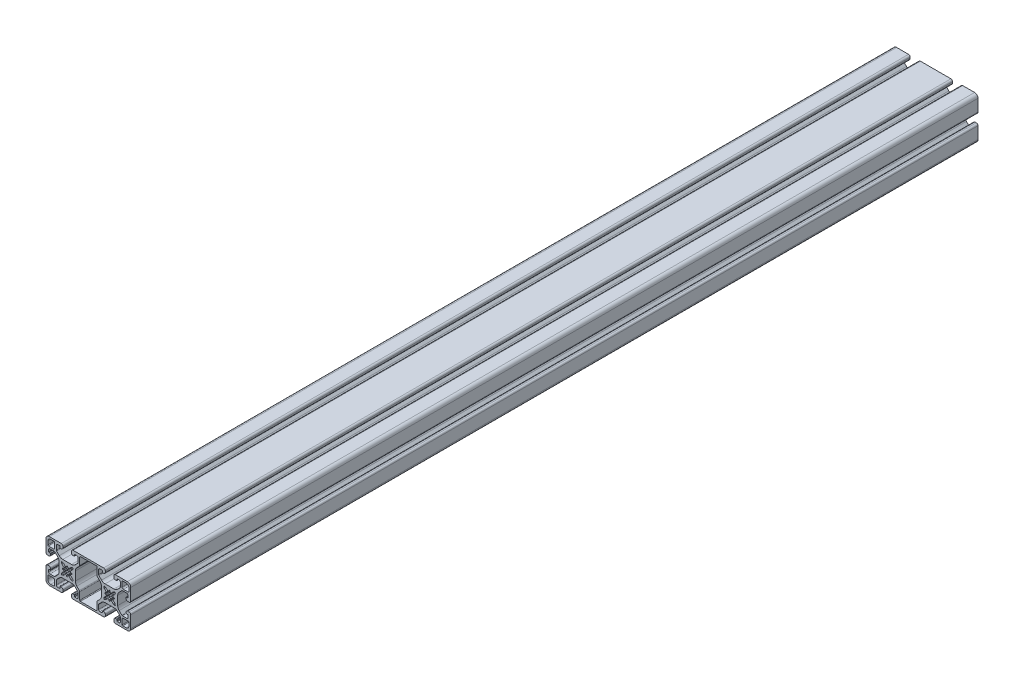
SolidWorks part; units mm, degrees
material "6105-T5 Aluminum"
ref_plane "Front Plane" through (0, 0, 0) normal (0, 0, 1) x (1, 0, 0)
ref_plane "Top Plane" through (0, 0, 0) normal (0, 1, 0) x (1, 0, 0)
ref_plane "Right Plane" through (0, 0, 0) normal (1, 0, 0) x (0, 0, -1)
sketch "Sketch1" plane through (0, 0, 0) normal (0, 0, 1) x (1, 0, 0)
  line L0 (-44, -18.4848) -> (-44, -17.255)
  line L1 (-46.474, -15.685) -> (-45.57, -15.685)
  line L2 (-56.83, -20) -> (-45.569, -20)
  line L3 (-46.855, -17.119) -> (-46.855, -16.066)
  line L4 (-60, -16.83) -> (-60, -5.57)
  line L5 (-49.015, -17.5) -> (-47.236, -17.5)
  line L6 (-58.43, -4) -> (-57.255, -4)
  line L7 (-50.285, -16.23) -> (-50.285, -12.2162)
  line L8 (-55.685, -5.57) -> (-55.685, -6.474)
  line L9 (-47.5137, -9.0762) -> (-50.0243, -11.5869)
  line L10 (-57.119, -6.855) -> (-56.066, -6.855)
  line L11 (-44.1549, -7.685) -> (-35.8451, -7.685)
  line L12 (-57.5, -9.015) -> (-57.5, -7.236)
  line L13 (-32.4863, -9.0762) -> (-29.9757, -11.5869)
  line L14 (-56.23, -10.285) -> (-52.2162, -10.285)
  line L15 (-29.715, -16.23) -> (-29.715, -12.2162)
  line L16 (-49.0762, -7.5137) -> (-51.5869, -10.0243)
  line L17 (-30.985, -17.5) -> (-32.764, -17.5)
  line L18 (-47.685, 4.1549) -> (-47.685, -4.1549)
  line L19 (-33.145, -17.119) -> (-33.145, -16.066)
  line L20 (-49.0762, 7.5137) -> (-51.5869, 10.0243)
  line L21 (-34.43, -15.685) -> (-33.526, -15.685)
  line L22 (-56.23, 10.285) -> (-52.2162, 10.285)
  line L23 (-36, -18.4848) -> (-36, -17.255)
  line L24 (-57.5, 9.015) -> (-57.5, 7.236)
  line L25 (-5.57, -20) -> (-34.431, -20)
  line L26 (-57.119, 6.855) -> (-56.066, 6.855)
  line L27 (-4, -17.255) -> (-4, -18.43)
  line L28 (-55.685, 6.474) -> (-55.685, 5.57)
  line L29 (-5.57, -15.685) -> (-6.474, -15.685)
  line L30 (-58.43, 4) -> (-57.255, 4)
  line L31 (-6.855, -17.119) -> (-6.855, -16.066)
  line L32 (-60, 16.83) -> (-60, 5.57)
  line L33 (-9.015, -17.5) -> (-7.236, -17.5)
  line L34 (-56.83, 20) -> (-45.57, 20)
  line L35 (-10.285, -16.23) -> (-10.285, -12.2162)
  line L36 (-44, 18.43) -> (-44, 17.255)
  line L37 (-7.5137, -9.0762) -> (-10.0243, -11.5869)
  line L38 (-45.57, 15.685) -> (-46.474, 15.685)
  line L39 (4.1549, -7.685) -> (-4.1549, -7.685)
  line L40 (-46.855, 17.119) -> (-46.855, 16.066)
  line L41 (7.5137, -9.0762) -> (10.0243, -11.5869)
  line L42 (-49.015, 17.5) -> (-47.236, 17.5)
  line L43 (10.285, -16.23) -> (10.285, -12.2162)
  line L44 (-50.285, 16.23) -> (-50.285, 12.2162)
  line L45 (9.015, -17.5) -> (7.236, -17.5)
  line L46 (-47.5137, 9.0762) -> (-50.0243, 11.5869)
  line L47 (6.855, -17.119) -> (6.855, -16.066)
  line L48 (-35.8451, 7.685) -> (-44.1549, 7.685)
  line L49 (6.474, -15.685) -> (5.57, -15.685)
  line L50 (-32.4863, 9.0762) -> (-29.9757, 11.5869)
  line L51 (4, -17.255) -> (4, -18.43)
  line L52 (-29.715, 16.23) -> (-29.715, 12.2162)
  line L53 (16.83, -20) -> (5.57, -20)
  line L54 (-30.985, 17.5) -> (-32.764, 17.5)
  line L55 (20, -16.83) -> (20, -5.57)
  line L56 (-33.145, 17.119) -> (-33.145, 16.066)
  line L57 (17.255, -4) -> (18.43, -4)
  line L58 (-33.526, 15.685) -> (-34.43, 15.685)
  line L59 (15.685, -5.57) -> (15.685, -6.474)
  line L60 (-36, 18.43) -> (-36, 17.255)
  line L61 (17.119, -6.855) -> (16.066, -6.855)
  line L62 (-34.43, 20) -> (-5.57, 20)
  line L63 (17.5, -9.015) -> (17.5, -7.236)
  line L64 (-4, 18.43) -> (-4, 17.255)
  line L65 (16.23, -10.285) -> (12.2162, -10.285)
  line L66 (-6.474, 15.685) -> (-5.57, 15.685)
  line L67 (9.0762, -7.5137) -> (11.5869, -10.0243)
  line L68 (-6.855, 17.119) -> (-6.855, 16.066)
  line L69 (7.685, 4.1549) -> (7.685, -4.1549)
  line L70 (-9.015, 17.5) -> (-7.236, 17.5)
  line L71 (9.0762, 7.5137) -> (11.5869, 10.0243)
  line L72 (-10.285, 16.23) -> (-10.285, 12.2162)
  line L73 (16.23, 10.285) -> (12.2162, 10.285)
  line L74 (-7.5137, 9.0762) -> (-10.0243, 11.5869)
  line L75 (17.5, 9.015) -> (17.5, 7.236)
  line L76 (-4.1549, 7.685) -> (4.1549, 7.685)
  line L77 (17.119, 6.855) -> (16.066, 6.855)
  line L78 (7.5137, 9.0762) -> (10.0243, 11.5869)
  line L79 (15.685, 6.474) -> (15.685, 5.57)
  line L80 (10.285, 16.23) -> (10.285, 12.2162)
  line L81 (17.255, 4) -> (18.43, 4)
  line L82 (9.015, 17.5) -> (7.236, 17.5)
  line L83 (20, 16.83) -> (20, 5.57)
  line L84 (6.855, 17.119) -> (6.855, 16.066)
  line L85 (16.83, 20) -> (5.57, 20)
  line L86 (5.57, 15.685) -> (6.474, 15.685)
  line L87 (4, 18.43) -> (4, 17.255)
  line L88 (15.545, -18.345) -> (12.4898, -18.345)
  line L89 (18.345, -12.4898) -> (18.345, -15.545)
  line L90 (11.8598, -17.715) -> (11.8598, -13.1298)
  line L91 (13.1298, -11.8598) -> (17.715, -11.8598)
  line L92 (-11.8598, 17.715) -> (-11.8598, 10.8233)
  line L93 (-11.4878, 9.9253) -> (-9.0762, 7.5137)
  line L94 (-27.5102, 18.345) -> (-12.4898, 18.345)
  line L95 (-7.685, 4.1549) -> (-7.685, -4.1549)
  line L96 (-28.1402, 10.8233) -> (-28.1402, 17.715)
  line L97 (-9.0762, -7.5137) -> (-11.4878, -9.9253)
  line L98 (-30.9238, 7.5137) -> (-28.5122, 9.9253)
  line L99 (-11.8598, -10.8233) -> (-11.8598, -17.715)
  line L100 (-32.315, -4.1549) -> (-32.315, 4.1549)
  line L101 (-12.4898, -18.345) -> (-27.5102, -18.345)
  line L102 (-28.5122, -9.9253) -> (-30.9238, -7.5137)
  line L103 (-28.1402, -17.715) -> (-28.1402, -10.8233)
  line L104 (-58.345, -15.545) -> (-58.345, -12.4898)
  line L105 (-52.4898, -18.345) -> (-55.545, -18.345)
  line L106 (-57.715, -11.8598) -> (-53.1298, -11.8598)
  line L107 (-51.8598, -13.1298) -> (-51.8598, -17.715)
  line L108 (-55.545, 18.345) -> (-52.4898, 18.345)
  line L109 (-58.345, 12.4898) -> (-58.345, 15.545)
  line L110 (-51.8598, 17.715) -> (-51.8598, 13.1298)
  line L111 (-53.1298, 11.8598) -> (-57.715, 11.8598)
  line L112 (18.345, 15.545) -> (18.345, 12.4898)
  line L113 (12.4898, 18.345) -> (15.545, 18.345)
  line L114 (17.715, 11.8598) -> (13.1298, 11.8598)
  line L115 (11.8598, 13.1298) -> (11.8598, 17.715)
  line L116 (-34.8737, -3.712) -> (-34.5607, -4.8481)
  line L117 (-36.9951, -1.5907) -> (-34.8737, -3.712)
  line L118 (-35.1519, -5.4393) -> (-36.288, -5.1263)
  line L119 (-36.288, -5.1263) -> (-38.4093, -3.0049)
  line L120 (-35.9124, -0.4923) -> (-36.6579, -0.625)
  line L121 (-39.375, -3.3421) -> (-39.5077, -4.0876)
  line L122 (-36.6579, 0.625) -> (-35.9124, 0.4923)
  line L123 (-40.4923, -4.0876) -> (-40.625, -3.3421)
  line L124 (-34.8737, 3.712) -> (-36.9951, 1.5907)
  line L125 (-34.5607, 4.8481) -> (-34.8737, 3.712)
  line L126 (-41.5907, -3.0049) -> (-43.712, -5.1263)
  line L127 (-43.712, -5.1263) -> (-44.8481, -5.4393)
  line L128 (-36.288, 5.1263) -> (-35.1519, 5.4393)
  line L129 (-38.4093, 3.0049) -> (-36.288, 5.1263)
  line L130 (-45.4393, -4.8481) -> (-45.1263, -3.712)
  line L131 (-45.1263, -3.712) -> (-43.0049, -1.5907)
  line L132 (-39.5077, 4.0876) -> (-39.375, 3.3421)
  line L133 (-43.3421, -0.625) -> (-44.0876, -0.4923)
  line L134 (-40.625, 3.3421) -> (-40.4923, 4.0876)
  line L135 (-44.0876, 0.4923) -> (-43.3421, 0.625)
  line L136 (-43.712, 5.1263) -> (-41.5907, 3.0049)
  line L137 (-44.8481, 5.4393) -> (-43.712, 5.1263)
  line L138 (-43.0049, 1.5907) -> (-45.1263, 3.712)
  line L139 (-45.1263, 3.712) -> (-45.4393, 4.8481)
  line L140 (5.1263, -3.712) -> (5.4393, -4.8481)
  line L141 (3.0049, -1.5907) -> (5.1263, -3.712)
  line L142 (4.8481, -5.4393) -> (3.712, -5.1263)
  line L143 (3.712, -5.1263) -> (1.5907, -3.0049)
  line L144 (4.0876, -0.4923) -> (3.3421, -0.625)
  line L145 (0.625, -3.3421) -> (0.4923, -4.0876)
  line L146 (3.3421, 0.625) -> (4.0876, 0.4923)
  line L147 (-0.4923, -4.0876) -> (-0.625, -3.3421)
  line L148 (5.1263, 3.712) -> (3.0049, 1.5907)
  line L149 (5.4393, 4.8481) -> (5.1263, 3.712)
  line L150 (-1.5907, -3.0049) -> (-3.712, -5.1263)
  line L151 (-3.712, -5.1263) -> (-4.8481, -5.4393)
  line L152 (3.712, 5.1263) -> (4.8481, 5.4393)
  line L153 (1.5907, 3.0049) -> (3.712, 5.1263)
  line L154 (-5.4393, -4.8481) -> (-5.1263, -3.712)
  line L155 (-5.1263, -3.712) -> (-3.0049, -1.5907)
  line L156 (0.4923, 4.0876) -> (0.625, 3.3421)
  line L157 (-3.3421, -0.625) -> (-4.0876, -0.4923)
  line L158 (-0.625, 3.3421) -> (-0.4923, 4.0876)
  line L159 (-4.0876, 0.4923) -> (-3.3421, 0.625)
  line L160 (-3.712, 5.1263) -> (-1.5907, 3.0049)
  line L161 (-4.8481, 5.4393) -> (-3.712, 5.1263)
  line L162 (-3.0049, 1.5907) -> (-5.1263, 3.712)
  line L163 (-5.1263, 3.712) -> (-5.4393, 4.8481)
  arc A0 (-44, -17.255) -> (-45.57, -15.685) centre (-45.57, -17.255) ccw
  arc A1 (-45.569, -20) -> (-44, -18.4848) centre (-45.569, -18.43) ccw
  arc A2 (-46.474, -15.685) -> (-46.855, -16.066) centre (-46.474, -16.066) ccw
  arc A3 (-60, -16.83) -> (-56.83, -20) centre (-56.83, -16.83) ccw
  arc A4 (-47.236, -17.5) -> (-46.855, -17.119) centre (-47.236, -17.119) ccw
  arc A5 (-58.43, -4) -> (-60, -5.57) centre (-58.43, -5.57) ccw
  arc A6 (-50.285, -16.23) -> (-49.015, -17.5) centre (-49.015, -16.23) ccw
  arc A7 (-55.685, -5.57) -> (-57.255, -4) centre (-57.255, -5.57) ccw
  arc A8 (-50.0243, -11.5869) -> (-50.285, -12.2162) centre (-49.395, -12.2162) ccw
  arc A9 (-56.066, -6.855) -> (-55.685, -6.474) centre (-56.066, -6.474) ccw
  arc A10 (-44.1549, -7.685) -> (-47.5137, -9.0762) centre (-44.1549, -12.435) ccw
  arc A11 (-57.119, -6.855) -> (-57.5, -7.236) centre (-57.119, -7.236) ccw
  arc A12 (-32.4863, -9.0762) -> (-35.8451, -7.685) centre (-35.8451, -12.435) ccw
  arc A13 (-57.5, -9.015) -> (-56.23, -10.285) centre (-56.23, -9.015) ccw
  arc A14 (-29.715, -12.2162) -> (-29.9757, -11.5869) centre (-30.605, -12.2162) ccw
  arc A15 (-52.2162, -10.285) -> (-51.5869, -10.0243) centre (-52.2162, -9.395) ccw
  arc A16 (-30.985, -17.5) -> (-29.715, -16.23) centre (-30.985, -16.23) ccw
  arc A17 (-49.0762, -7.5137) -> (-47.685, -4.1549) centre (-52.435, -4.1549) ccw
  arc A18 (-33.145, -17.119) -> (-32.764, -17.5) centre (-32.764, -17.119) ccw
  arc A19 (-47.685, 4.1549) -> (-49.0762, 7.5137) centre (-52.435, 4.1549) ccw
  arc A20 (-33.145, -16.066) -> (-33.526, -15.685) centre (-33.526, -16.066) ccw
  arc A21 (-51.5869, 10.0243) -> (-52.2162, 10.285) centre (-52.2162, 9.395) ccw
  arc A22 (-34.43, -15.685) -> (-36, -17.255) centre (-34.43, -17.255) ccw
  arc A23 (-56.23, 10.285) -> (-57.5, 9.015) centre (-56.23, 9.015) ccw
  arc A24 (-36, -18.4848) -> (-34.431, -20) centre (-34.431, -18.43) ccw
  arc A25 (-57.5, 7.236) -> (-57.119, 6.855) centre (-57.119, 7.236) ccw
  arc A26 (-5.57, -20) -> (-4, -18.43) centre (-5.57, -18.43) ccw
  arc A27 (-55.685, 6.474) -> (-56.066, 6.855) centre (-56.066, 6.474) ccw
  arc A28 (-4, -17.255) -> (-5.57, -15.685) centre (-5.57, -17.255) ccw
  arc A29 (-57.255, 4) -> (-55.685, 5.57) centre (-57.255, 5.57) ccw
  arc A30 (-6.474, -15.685) -> (-6.855, -16.066) centre (-6.474, -16.066) ccw
  arc A31 (-60, 5.57) -> (-58.43, 4) centre (-58.43, 5.57) ccw
  arc A32 (-7.236, -17.5) -> (-6.855, -17.119) centre (-7.236, -17.119) ccw
  arc A33 (-56.83, 20) -> (-60, 16.83) centre (-56.83, 16.83) ccw
  arc A34 (-10.285, -16.23) -> (-9.015, -17.5) centre (-9.015, -16.23) ccw
  arc A35 (-44, 18.43) -> (-45.57, 20) centre (-45.57, 18.43) ccw
  arc A36 (-10.0243, -11.5869) -> (-10.285, -12.2162) centre (-9.395, -12.2162) ccw
  arc A37 (-45.57, 15.685) -> (-44, 17.255) centre (-45.57, 17.255) ccw
  arc A38 (-4.1549, -7.685) -> (-7.5137, -9.0762) centre (-4.1549, -12.435) ccw
  arc A39 (-46.855, 16.066) -> (-46.474, 15.685) centre (-46.474, 16.066) ccw
  arc A40 (7.5137, -9.0762) -> (4.1549, -7.685) centre (4.1549, -12.435) ccw
  arc A41 (-46.855, 17.119) -> (-47.236, 17.5) centre (-47.236, 17.119) ccw
  arc A42 (10.285, -12.2162) -> (10.0243, -11.5869) centre (9.395, -12.2162) ccw
  arc A43 (-49.015, 17.5) -> (-50.285, 16.23) centre (-49.015, 16.23) ccw
  arc A44 (9.015, -17.5) -> (10.285, -16.23) centre (9.015, -16.23) ccw
  arc A45 (-50.285, 12.2162) -> (-50.0243, 11.5869) centre (-49.395, 12.2162) ccw
  arc A46 (6.855, -17.119) -> (7.236, -17.5) centre (7.236, -17.119) ccw
  arc A47 (-47.5137, 9.0762) -> (-44.1549, 7.685) centre (-44.1549, 12.435) ccw
  arc A48 (6.855, -16.066) -> (6.474, -15.685) centre (6.474, -16.066) ccw
  arc A49 (-35.8451, 7.685) -> (-32.4863, 9.0762) centre (-35.8451, 12.435) ccw
  arc A50 (5.57, -15.685) -> (4, -17.255) centre (5.57, -17.255) ccw
  arc A51 (-29.9757, 11.5869) -> (-29.715, 12.2162) centre (-30.605, 12.2162) ccw
  arc A52 (4, -18.43) -> (5.57, -20) centre (5.57, -18.43) ccw
  arc A53 (-29.715, 16.23) -> (-30.985, 17.5) centre (-30.985, 16.23) ccw
  arc A54 (16.83, -20) -> (20, -16.83) centre (16.83, -16.83) ccw
  arc A55 (-32.764, 17.5) -> (-33.145, 17.119) centre (-32.764, 17.119) ccw
  arc A56 (20, -5.57) -> (18.43, -4) centre (18.43, -5.57) ccw
  arc A57 (-33.526, 15.685) -> (-33.145, 16.066) centre (-33.526, 16.066) ccw
  arc A58 (17.255, -4) -> (15.685, -5.57) centre (17.255, -5.57) ccw
  arc A59 (-36, 17.255) -> (-34.43, 15.685) centre (-34.43, 17.255) ccw
  arc A60 (15.685, -6.474) -> (16.066, -6.855) centre (16.066, -6.474) ccw
  arc A61 (-34.43, 20) -> (-36, 18.43) centre (-34.43, 18.43) ccw
  arc A62 (17.5, -7.236) -> (17.119, -6.855) centre (17.119, -7.236) ccw
  arc A63 (-4, 18.43) -> (-5.57, 20) centre (-5.57, 18.43) ccw
  arc A64 (16.23, -10.285) -> (17.5, -9.015) centre (16.23, -9.015) ccw
  arc A65 (-5.57, 15.685) -> (-4, 17.255) centre (-5.57, 17.255) ccw
  arc A66 (11.5869, -10.0243) -> (12.2162, -10.285) centre (12.2162, -9.395) ccw
  arc A67 (-6.855, 16.066) -> (-6.474, 15.685) centre (-6.474, 16.066) ccw
  arc A68 (7.685, -4.1549) -> (9.0762, -7.5137) centre (12.435, -4.1549) ccw
  arc A69 (-6.855, 17.119) -> (-7.236, 17.5) centre (-7.236, 17.119) ccw
  arc A70 (9.0762, 7.5137) -> (7.685, 4.1549) centre (12.435, 4.1549) ccw
  arc A71 (-9.015, 17.5) -> (-10.285, 16.23) centre (-9.015, 16.23) ccw
  arc A72 (12.2162, 10.285) -> (11.5869, 10.0243) centre (12.2162, 9.395) ccw
  arc A73 (-10.285, 12.2162) -> (-10.0243, 11.5869) centre (-9.395, 12.2162) ccw
  arc A74 (17.5, 9.015) -> (16.23, 10.285) centre (16.23, 9.015) ccw
  arc A75 (-7.5137, 9.0762) -> (-4.1549, 7.685) centre (-4.1549, 12.435) ccw
  arc A76 (17.119, 6.855) -> (17.5, 7.236) centre (17.119, 7.236) ccw
  arc A77 (4.1549, 7.685) -> (7.5137, 9.0762) centre (4.1549, 12.435) ccw
  arc A78 (16.066, 6.855) -> (15.685, 6.474) centre (16.066, 6.474) ccw
  arc A79 (10.0243, 11.5869) -> (10.285, 12.2162) centre (9.395, 12.2162) ccw
  arc A80 (15.685, 5.57) -> (17.255, 4) centre (17.255, 5.57) ccw
  arc A81 (10.285, 16.23) -> (9.015, 17.5) centre (9.015, 16.23) ccw
  arc A82 (18.43, 4) -> (20, 5.57) centre (18.43, 5.57) ccw
  arc A83 (7.236, 17.5) -> (6.855, 17.119) centre (7.236, 17.119) ccw
  arc A84 (20, 16.83) -> (16.83, 20) centre (16.83, 16.83) ccw
  arc A85 (6.474, 15.685) -> (6.855, 16.066) centre (6.474, 16.066) ccw
  arc A86 (5.57, 20) -> (4, 18.43) centre (5.57, 18.43) ccw
  arc A87 (4, 17.255) -> (5.57, 15.685) centre (5.57, 17.255) ccw
  arc A88 (15.545, -18.345) -> (18.345, -15.545) centre (15.545, -15.545) ccw
  arc A89 (11.8598, -17.715) -> (12.4898, -18.345) centre (12.4898, -17.715) ccw
  arc A90 (18.345, -12.4898) -> (17.715, -11.8598) centre (17.715, -12.4898) ccw
  arc A91 (13.1298, -11.8598) -> (11.8598, -13.1298) centre (13.1298, -13.1298) ccw
  arc A92 (-11.8598, 10.8233) -> (-11.4878, 9.9253) centre (-10.5898, 10.8233) ccw
  arc A93 (-11.8598, 17.715) -> (-12.4898, 18.345) centre (-12.4898, 17.715) ccw
  arc A94 (-7.685, 4.1549) -> (-9.0762, 7.5137) centre (-12.435, 4.1549) ccw
  arc A95 (-27.5102, 18.345) -> (-28.1402, 17.715) centre (-27.5102, 17.715) ccw
  arc A96 (-9.0762, -7.5137) -> (-7.685, -4.1549) centre (-12.435, -4.1549) ccw
  arc A97 (-28.5122, 9.9253) -> (-28.1402, 10.8233) centre (-29.4102, 10.8233) ccw
  arc A98 (-11.4878, -9.9253) -> (-11.8598, -10.8233) centre (-10.5898, -10.8233) ccw
  arc A99 (-30.9238, 7.5137) -> (-32.315, 4.1549) centre (-27.565, 4.1549) ccw
  arc A100 (-12.4898, -18.345) -> (-11.8598, -17.715) centre (-12.4898, -17.715) ccw
  arc A101 (-32.315, -4.1549) -> (-30.9238, -7.5137) centre (-27.565, -4.1549) ccw
  arc A102 (-28.1402, -17.715) -> (-27.5102, -18.345) centre (-27.5102, -17.715) ccw
  arc A103 (-28.1402, -10.8233) -> (-28.5122, -9.9253) centre (-29.4102, -10.8233) ccw
  arc A104 (-58.345, -15.545) -> (-55.545, -18.345) centre (-55.545, -15.545) ccw
  arc A105 (-57.715, -11.8598) -> (-58.345, -12.4898) centre (-57.715, -12.4898) ccw
  arc A106 (-52.4898, -18.345) -> (-51.8598, -17.715) centre (-52.4898, -17.715) ccw
  arc A107 (-51.8598, -13.1298) -> (-53.1298, -11.8598) centre (-53.1298, -13.1298) ccw
  arc A108 (-55.545, 18.345) -> (-58.345, 15.545) centre (-55.545, 15.545) ccw
  arc A109 (-51.8598, 17.715) -> (-52.4898, 18.345) centre (-52.4898, 17.715) ccw
  arc A110 (-58.345, 12.4898) -> (-57.715, 11.8598) centre (-57.715, 12.4898) ccw
  arc A111 (-53.1298, 11.8598) -> (-51.8598, 13.1298) centre (-53.1298, 13.1298) ccw
  arc A112 (18.345, 15.545) -> (15.545, 18.345) centre (15.545, 15.545) ccw
  arc A113 (17.715, 11.8598) -> (18.345, 12.4898) centre (17.715, 12.4898) ccw
  arc A114 (12.4898, 18.345) -> (11.8598, 17.715) centre (12.4898, 17.715) ccw
  arc A115 (11.8598, 13.1298) -> (13.1298, 11.8598) centre (13.1298, 13.1298) ccw
  arc A116 (-35.1519, -5.4393) -> (-34.5607, -4.8481) centre (-35.0503, -4.9497) ccw
  arc A117 (-36.9951, -1.5907) -> (-36.6579, -0.625) centre (-40, 0) ccw
  arc A118 (-39.375, -3.3421) -> (-38.4093, -3.0049) centre (-40, 0) ccw
  arc A119 (-35.9124, -0.4923) -> (-35.9124, 0.4923) centre (-36, 0) ccw
  arc A120 (-40.4923, -4.0876) -> (-39.5077, -4.0876) centre (-40, -4) ccw
  arc A121 (-36.6579, 0.625) -> (-36.9951, 1.5907) centre (-40, 0) ccw
  arc A122 (-41.5907, -3.0049) -> (-40.625, -3.3421) centre (-40, 0) ccw
  arc A123 (-34.5607, 4.8481) -> (-35.1519, 5.4393) centre (-35.0503, 4.9497) ccw
  arc A124 (-45.4393, -4.8481) -> (-44.8481, -5.4393) centre (-44.9497, -4.9497) ccw
  arc A125 (-38.4093, 3.0049) -> (-39.375, 3.3421) centre (-40, 0) ccw
  arc A126 (-43.3421, -0.625) -> (-43.0049, -1.5907) centre (-40, 0) ccw
  arc A127 (-39.5077, 4.0876) -> (-40.4923, 4.0876) centre (-40, 4) ccw
  arc A128 (-44.0876, 0.4923) -> (-44.0876, -0.4923) centre (-44, 0) ccw
  arc A129 (-40.625, 3.3421) -> (-41.5907, 3.0049) centre (-40, 0) ccw
  arc A130 (-43.0049, 1.5907) -> (-43.3421, 0.625) centre (-40, 0) ccw
  arc A131 (-44.8481, 5.4393) -> (-45.4393, 4.8481) centre (-44.9497, 4.9497) ccw
  arc A132 (4.8481, -5.4393) -> (5.4393, -4.8481) centre (4.9497, -4.9497) ccw
  arc A133 (3.0049, -1.5907) -> (3.3421, -0.625) centre (0, 0) ccw
  arc A134 (0.625, -3.3421) -> (1.5907, -3.0049) centre (0, 0) ccw
  arc A135 (4.0876, -0.4923) -> (4.0876, 0.4923) centre (4, 0) ccw
  arc A136 (-0.4923, -4.0876) -> (0.4923, -4.0876) centre (0, -4) ccw
  arc A137 (3.3421, 0.625) -> (3.0049, 1.5907) centre (0, 0) ccw
  arc A138 (-1.5907, -3.0049) -> (-0.625, -3.3421) centre (0, 0) ccw
  arc A139 (5.4393, 4.8481) -> (4.8481, 5.4393) centre (4.9497, 4.9497) ccw
  arc A140 (-5.4393, -4.8481) -> (-4.8481, -5.4393) centre (-4.9497, -4.9497) ccw
  arc A141 (1.5907, 3.0049) -> (0.625, 3.3421) centre (0, 0) ccw
  arc A142 (-3.3421, -0.625) -> (-3.0049, -1.5907) centre (0, 0) ccw
  arc A143 (0.4923, 4.0876) -> (-0.4923, 4.0876) centre (0, 4) ccw
  arc A144 (-4.0876, 0.4923) -> (-4.0876, -0.4923) centre (-4, 0) ccw
  arc A145 (-0.625, 3.3421) -> (-1.5907, 3.0049) centre (0, 0) ccw
  arc A146 (-3.0049, 1.5907) -> (-3.3421, 0.625) centre (0, 0) ccw
  arc A147 (-4.8481, 5.4393) -> (-5.4393, 4.8481) centre (-4.9497, 4.9497) ccw
extrude "Extrude1" add sketch "Sketch1" against normal blind 800
